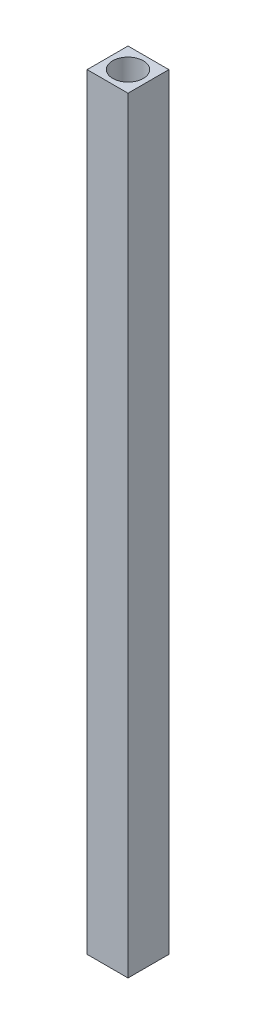
SolidWorks part; units mm, degrees
ref_plane "前视基准面" through (0, 0, 0) normal (0, 0, 1) x (1, 0, 0)
ref_plane "上视基准面" through (0, 0, 0) normal (0, 1, 0) x (1, 0, 0)
ref_plane "右视基准面" through (0, 0, 0) normal (1, 0, 0) x (0, 0, -1)
sketch "草图1" plane through (0, 0, 0) normal (0, 1, 0) x (1, 0, 0)
  line L1 (-4, -4) -> (4, -4)
  line L2 (-4, -4) -> (-4, 4)
  line L3 (-4, 4) -> (4, 4)
  line L4 (4, -4) -> (4, 4)
  line L5 (-4, -4) -> (4, 4) construction
  line L6 (-4, 4) -> (4, -4) construction
  circle A0 centre (0, 0) radius 3
  point P0 (0, 0)
  dimension "D3" = 6
  dimension "D1" = 8
  dimension "D2" = 8
extrude "凸台-拉伸1" add sketch "草图1" along normal blind 150
